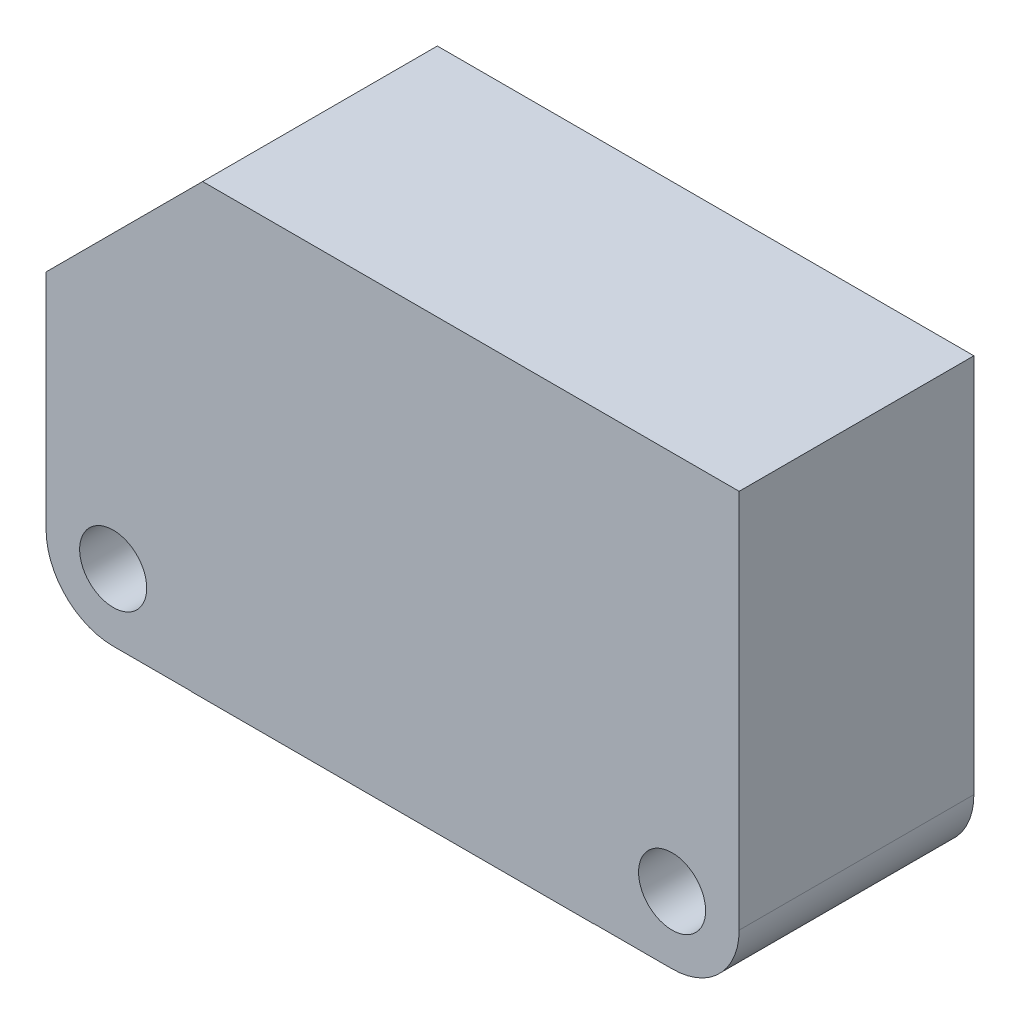
SolidWorks part; units mm, degrees
ref_plane "Plan de face" through (0, 0, 0) normal (0, 0, 1) x (1, 0, 0)
ref_plane "Plan de dessus" through (0, 0, 0) normal (0, 1, 0) x (1, 0, 0)
ref_plane "Plan de droite" through (0, 0, 0) normal (1, 0, 0) x (0, 0, -1)
sketch "Esquisse1" plane through (0, 0, 0) normal (0, 0, 1) x (1, 0, 0)
  line L0 (0, 0) -> (31, 0)
  line L1 (31, 0) -> (31, 20)
  line L2 (31, 20) -> (7, 20)
  line L3 (7, 20) -> (0, 13)
  line L4 (0, 13) -> (0, 0)
  dimension "D1" = 31
  dimension "D2" = 20
  dimension "D3" = 24
  dimension "D4" = 45
extrude "Boss.-Extru.1" add sketch "Esquisse1" against normal blind 10.5
sketch "Esquisse2" plane through (0, 0, 0) normal (0, 0, 1) x (1, 0, 0)
  line L0 (31, 0) -> (31, 20) construction
  line L1 (0, 0) -> (31, 0) construction
  line L2 (0, 13) -> (0, 0) construction
  circle A0 centre (3, 3) radius 1.5
  circle A1 centre (28, 3) radius 1.5
  dimension "D1" = 3
  dimension "D2" = 3
  dimension "D3" = 3
  dimension "D4" = 3
  dimension "D5" = 3
  dimension "D6" = 3
extrude "Enlèv. mat.-Extru.1" cut sketch "Esquisse2" against normal through all
fillet "Congé1" radius 3 2 edges at (31, 0, -5.25) (0, 0, -5.25)
sketch "Esquisse3" plane through (0, 0, 0) normal (0, -1, 0) x (1, 0, 0)
  line L0 (6.5, 0) -> (6.5, -10.5)
  line L1 (3, 0) -> (28, 0) construction
  line L2 (3, -10.5) -> (28, -10.5) construction
  line L3 (6.5, -10.5) -> (24.5, -10.5)
  line L4 (24.5, -10.5) -> (24.5, 0)
  line L5 (24.5, 0) -> (6.5, 0)
  line L6 (31, 0) -> (31, -10.5) construction
  dimension "D1" = 18
  dimension "D2" = 6.5
extrude "Boss.-Extru.2" add sketch "Esquisse3" along normal blind 0.01
